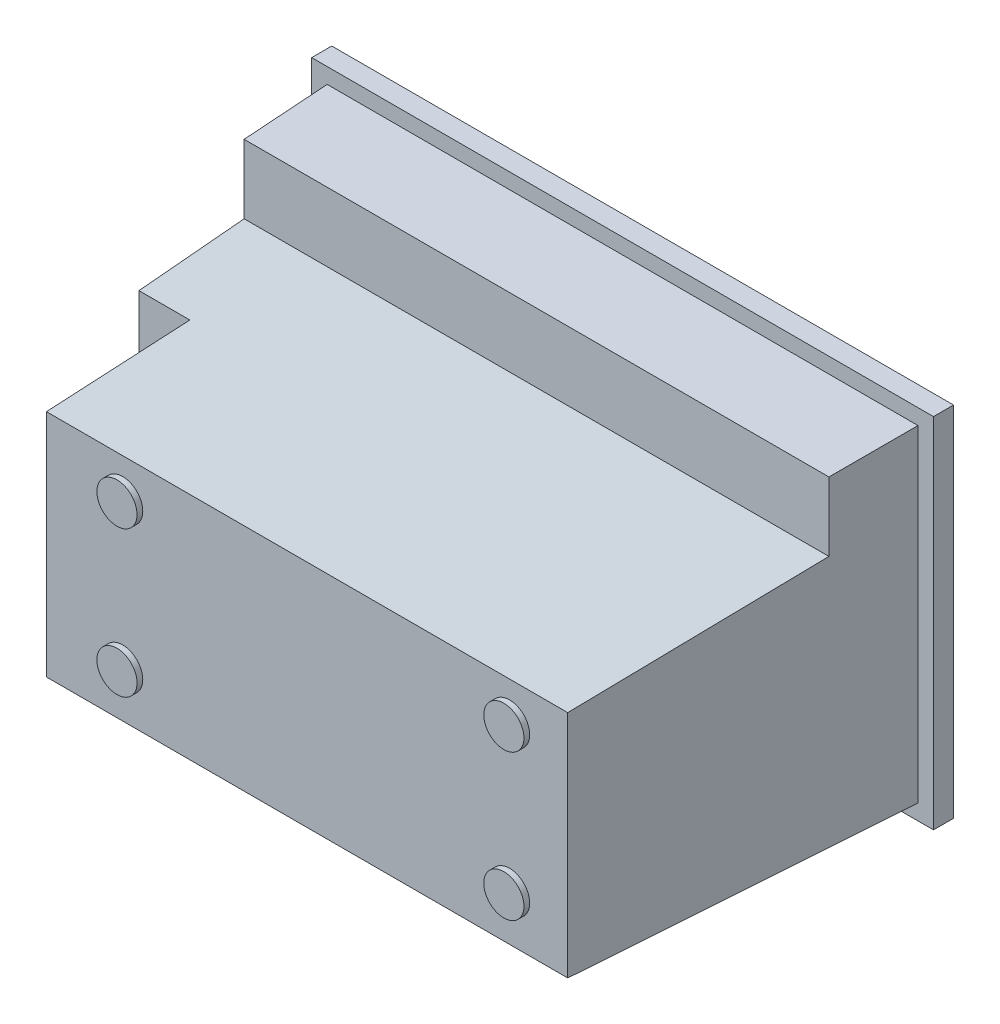
SolidWorks part; units mm, degrees
ref_plane "前视基准面" through (0, 0, 0) normal (0, 0, 1) x (1, 0, 0)
ref_plane "上视基准面" through (0, 0, 0) normal (0, 1, 0) x (1, 0, 0)
ref_plane "右视基准面" through (0, 0, 0) normal (1, 0, 0) x (0, 0, -1)
sketch "草图1" plane through (0, 0, 0) normal (0, 0, 1) x (1, 0, 0)
  line L0 (-81.6435, 0) -> (86.9014, 0) construction
  line L1 (-51.5, 28.5) -> (51.5, 28.5)
  line L2 (-51.5, 28.5) -> (-51.5, -28.5)
  line L3 (-51.5, -28.5) -> (51.5, -28.5)
  line L4 (51.5, 28.5) -> (51.5, -28.5)
  line L5 (0, 71.4198) -> (0, -57.1067) construction
  dimension "D1" = 103
  dimension "D2" = 57
extrude "拉伸1" add sketch "草图1" along normal blind 59 draft 2
sketch "草图2" plane through (0, 0, 59) normal (0, 0, 1) x (1, 0, 0)
  line L0 (-49.4397, 26.4397) -> (-49.4397, -26.4397) construction
  line L1 (-80.98, 46.4809) -> (-41.4397, 46.4809)
  line L2 (-80.98, 46.4809) -> (-80.98, -38.0681)
  line L3 (-80.98, -38.0681) -> (-41.4397, -38.0681)
  line L4 (-41.4397, 46.4809) -> (-41.4397, -38.0681)
  dimension "D1" = 8
extrude "切除-拉伸1" cut sketch "草图2" against normal blind 25
sketch "草图3" plane through (0, 0, 59) normal (0, 0, 1) x (1, 0, 0)
  line L1 (-28.1462, 6.9773) -> (39.3033, 6.9773) construction
  line L2 (-28.1462, 6.9773) -> (-28.1462, -18.4434) construction
  line L3 (-28.1462, -18.4434) -> (39.3033, -18.4434) construction
  line L4 (39.3033, 6.9773) -> (39.3033, -18.4434) construction
  circle A0 centre (-28.1462, 6.9773) radius 3.5
  circle A1 centre (39.3033, 6.9773) radius 3.5
  circle A2 centre (-28.1462, -18.4434) radius 3.5
  circle A3 centre (39.3033, -18.4434) radius 3.5
  dimension "D1" = 7
extrude "拉伸2" add sketch "草图3" along normal blind 1
sketch "草图4" plane through (0, 0, 0) normal (0, 0, -1) x (-1, 0, 0)
  line L8 (54.2, -31.2) -> (54.2, 31.2)
  line L9 (54.2, 31.2) -> (-54.2, 31.2)
  line L10 (-54.2, 31.2) -> (-54.2, -31.2)
  line L11 (-54.2, -31.2) -> (54.2, -31.2)
  line L12 (54.2, -31.2) -> (54.2, 31.2)
  line L13 (54.2, 31.2) -> (-54.2, 31.2)
  line L14 (-54.2, 31.2) -> (-54.2, -31.2)
  line L15 (-54.2, -31.2) -> (54.2, -31.2)
  dimension "D1" = 2.7
extrude "拉伸3" add sketch "草图4" along normal blind 3.5
sketch "草图5" plane through (0, 0, 0) normal (1, 0, 0) x (0, 0, -1)
  line L0 (-59, 13.6266) -> (-15, 15.9762)
  line L1 (-59, -26.4397) -> (-59, 26.4397) construction
  line L2 (-15, 15.9762) -> (-15, 27.9762)
  line L3 (-59, 26.4397) -> (0, 28.5) construction
  line L4 (-15, 27.9762) -> (-59, 29.6579)
  line L5 (-59, 29.6579) -> (-59, 13.6266)
  dimension "D1" = 44
  dimension "D2" = 12
extrude "切除-拉伸2" cut sketch "草图5" against normal through all and the other way through all
sketch "草图6" plane through (0, 0, -3.5) normal (0, 0, -1) x (-1, 0, 0)
  line L1 (-46.1674, -9.874) -> (43.143, -9.874)
  line L2 (-46.1674, -9.874) -> (-46.1674, -24.9962)
  line L3 (-46.1674, -24.9962) -> (43.143, -24.9962)
  line L4 (43.143, -9.874) -> (43.143, -24.9962)
extrude "切除-拉伸3" cut sketch "草图6" against normal blind 0.5
